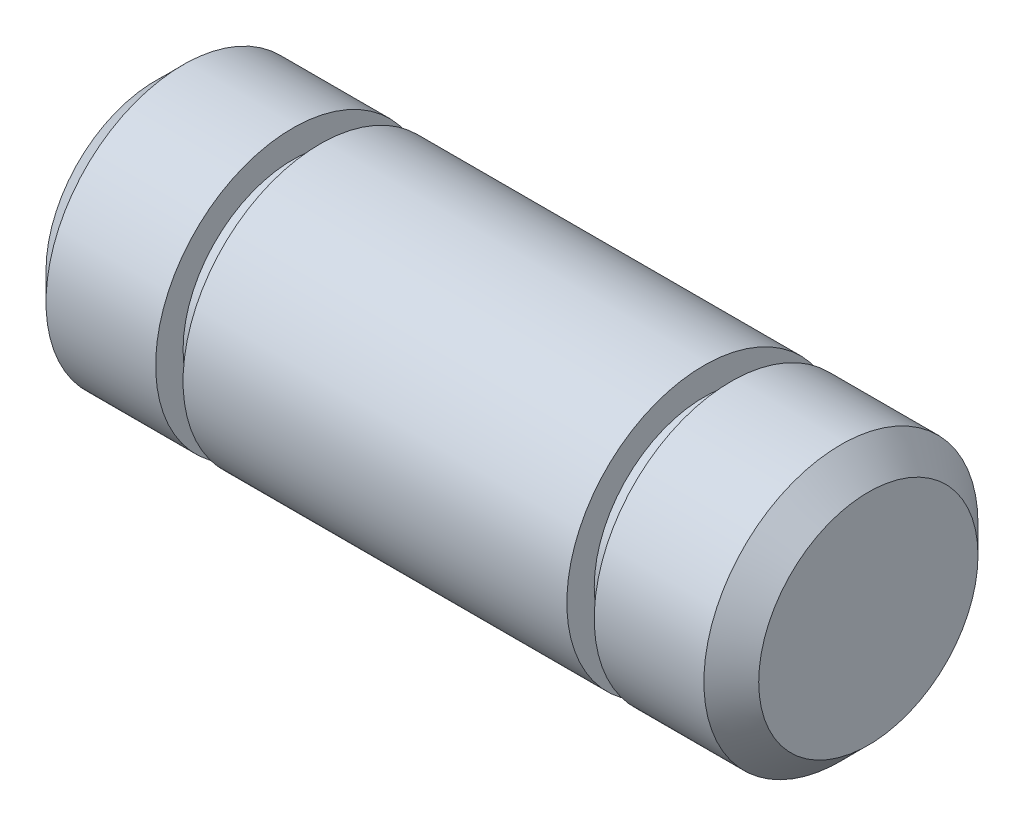
SolidWorks part; units mm, degrees
ref_plane "Front Plane" through (0, 0, 0) normal (0, 0, 1) x (1, 0, 0)
ref_plane "Top Plane" through (0, 0, 0) normal (0, 1, 0) x (1, 0, 0)
ref_plane "Right Plane" through (0, 0, 0) normal (1, 0, 0) x (0, 0, -1)
sketch "Sketch1" plane through (0, 0, 0) normal (0, 1, 0) x (1, 0, 0)
  line L0 (0, 0) -> (0, 4)
  line L1 (1, 5) -> (5, 5)
  line L2 (5, 5) -> (5, 4)
  line L3 (5, 4) -> (6, 4)
  line L4 (6, 4) -> (6, 5)
  line L5 (6, 5) -> (20, 5)
  line L6 (20, 5) -> (20, 4)
  line L7 (20, 4) -> (21, 4)
  line L8 (21, 4) -> (21, 5)
  line L9 (21, 5) -> (25, 5)
  line L10 (26, 4) -> (26, 0)
  line L11 (26, 0) -> (0, 0)
  line L12 (0, 4) -> (1, 5)
  line L13 (25, 5) -> (26, 4)
  point P1 (0, 5)
  point P13 (26, 5)
  dimension "D1" = 5
  dimension "D2" = 1
  dimension "D3" = 1
  dimension "D4" = 5
  dimension "D5" = 4
  dimension "26" = 26
  dimension "D6" = 5
revolve "Revolve1" add sketch "Sketch1" angle 360 about L11
